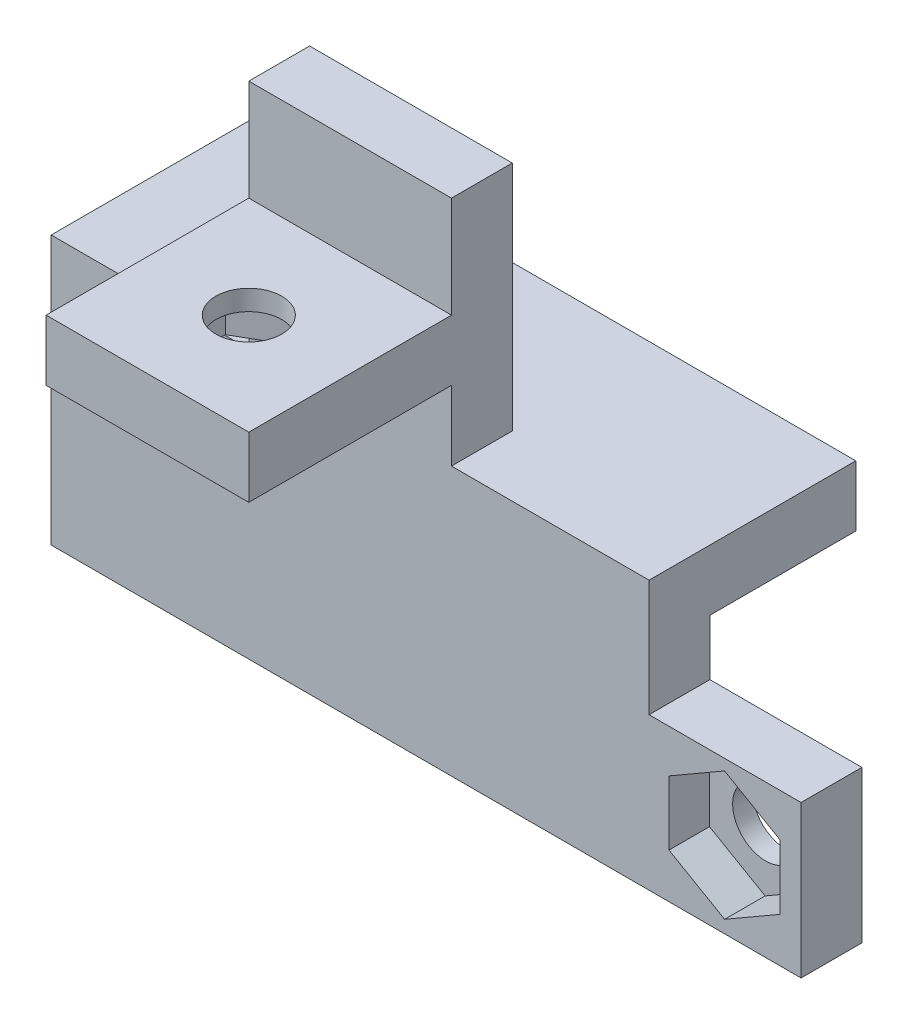
SolidWorks part; units mm, degrees
ref_plane "Alzado" through (0, 0, 0) normal (0, 0, 1) x (1, 0, 0)
ref_plane "Planta" through (0, 0, 0) normal (0, 1, 0) x (1, 0, 0)
ref_plane "Vista lateral" through (0, 0, 0) normal (1, 0, 0) x (0, 0, -1)
sketch "Croquis1" plane through (0, 0, 0) normal (0, 0, 1) x (1, 0, 0)
  line L0 (-40.4588, -20.95) -> (-40.4588, -24.7) construction
  line L1 (-40.4588, -24.7) -> (-77.4588, -24.7)
  line L2 (-77.4588, -14.45) -> (-47.9588, -14.45)
  line L4 (-40.4588, -24.7) -> (-40.4588, -17.2)
  line L5 (-40.4588, -17.2) -> (-47.9588, -17.2)
  line L7 (-47.9588, -17.2) -> (-47.9588, -14.45)
  line L8 (-77.4588, -24.7) -> (-77.4588, -14.45)
  circle A0 centre (-44.2088, -20.95) radius 1.625
  dimension "D1" = 3.25
  dimension "D2" = 40.4588
  dimension "D3" = 44.2088
  dimension "D4" = 47.9588
  dimension "D5" = 77.4588
  dimension "D6" = 14.45
  dimension "D7" = 17.2
extrude "Saliente-Extruir1" add sketch "Croquis1" along normal blind 3
sketch "Croquis2" plane through (0, 0, 3) normal (0, 0, 1) x (1, 0, 0)
  line L0 (-40.4588, -24.7) -> (-40.4588, -17.2) construction
  line L1 (-44.2325, -17.739) -> (-46.9778, -19.324)
  line L2 (-46.9778, -19.324) -> (-46.9778, -22.494)
  line L3 (-46.9778, -22.494) -> (-44.2325, -24.079)
  line L4 (-44.2325, -24.079) -> (-41.4872, -22.494)
  line L5 (-41.4872, -22.494) -> (-41.4872, -19.324)
  line L6 (-41.4872, -19.324) -> (-44.2325, -17.739)
  line L7 (-47.9588, -14.45) -> (-77.4588, -14.45) construction
  circle A0 centre (-44.2325, -20.909) radius 2.7453 construction
  dimension "D1" = 5.4906
  dimension "D2" = 1.0284
  dimension "D3" = 3.289
extrude "Cortar-Extruir1" cut sketch "Croquis2" against normal blind 2
sketch "Croquis4" plane through (0, -14.45, 0) normal (0, 1, 0) x (1, 0, 0)
  line L0 (-77.3588, 7.2) -> (-77.4588, 7.2) construction
  line L1 (-77.4588, -3) -> (-77.4588, 0) construction
  line L2 (-47.9588, -3) -> (-77.4588, -3)
  line L3 (-47.9588, -3) -> (-47.9588, 7.2)
  line L4 (-47.9588, 7.2) -> (-77.4588, 7.2)
  line L5 (-77.4588, -3) -> (-77.4588, 7.2)
  line L6 (-47.9588, 0) -> (-77.4588, 0) construction
  dimension "D1" = 29.5
  dimension "D2" = 7.2
  dimension "D3" = 3
extrude "Saliente-Extruir2" add sketch "Croquis4" along normal blind 3
sketch "Croquis6" plane through (0, 0, 3) normal (0, 0, 1) x (1, 0, 0)
  line L0 (-77.4588, -11.45) -> (-47.9588, -11.45) construction
  line L1 (-47.9588, -11.45) -> (-62.7088, -11.45) construction
  line L2 (-47.9588, -17.2) -> (-47.9588, -11.45) construction
  line L3 (-62.7088, -11.45) -> (-62.7088, -5) construction
  line L4 (-62.7088, -11.45) -> (-67.7088, -11.45)
  line L5 (-62.7088, -11.45) -> (-57.7088, -11.45)
  line L6 (-57.7088, -11.45) -> (-57.7088, -5)
  line L7 (-57.7088, -5) -> (-67.7088, -5)
  line L8 (-67.7088, -5) -> (-67.7088, -11.45)
  line L9 (-46.9778, -19.324) -> (-46.9778, -22.494) construction
  dimension "D1" = 10.731
  dimension "D2" = 12.739
extrude "Saliente-Extruir3" add sketch "Croquis6" against normal up to vertex (3 mm away)
sketch "Croquis7" plane through (0, -5, 0) normal (0, 1, 0) x (1, 0, 0)
  line L0 (-57.7088, 0) -> (-67.7088, 0) construction
  line L1 (-67.7088, 0) -> (-57.7088, 0)
  line L2 (-67.7088, 0) -> (-67.7088, -3)
  line L3 (-67.7088, -3) -> (-57.7088, -3)
  line L4 (-57.7088, 0) -> (-57.7088, -3)
  line L5 (-57.7088, 0) -> (-57.7088, -3) construction
  line L6 (-57.7088, -3) -> (-67.7088, -3) construction
  dimension "D1" = 10
extrude "Saliente-Extruir4" add sketch "Croquis7" along normal up to vertex (5 mm away)
sketch "Croquis9" plane through (0, 0, 3) normal (0, 0, 1) x (1, 0, 0)
  line L0 (-57.2795, -5) -> (-59.2014, -5) construction
  line L1 (-57.7088, -8) -> (-57.7088, -5)
  line L2 (-57.7088, -11.45) -> (-57.7088, 0) construction
  line L3 (-57.7088, -8) -> (-67.7088, -8)
  line L4 (-67.7088, 0) -> (-67.7088, -11.45) construction
  line L5 (-67.7088, -8) -> (-67.7088, -5)
  line L6 (-67.7088, -5) -> (-57.7088, -5)
  line L8 (-40.4588, -17.2) -> (-47.9588, -17.2) construction
  dimension "D1" = 9.2
  dimension "D2" = 12.2
extrude "Saliente-Extruir5" add sketch "Croquis9" along normal blind 10
sketch "Croquis10" plane through (0, -8, 0) normal (0, -1, 0) x (1, 0, 0)
  line L0 (-57.7088, 3) -> (-67.7088, 13) construction
  line L1 (-77.4588, 3) -> (-40.4588, 3) construction
  line L2 (-57.7088, 13) -> (-57.7088, 3) construction
  line L3 (-67.7088, 13) -> (-57.7088, 13) construction
  circle A0 centre (-62.7088, 8) radius 1.625
  dimension "D1" = 3.25
  dimension "D2" = 5
extrude "Cortar-Extruir2" cut sketch "Croquis10" against normal up to vertex (3 mm away)
sketch "Croquis11" plane through (0, -8, 0) normal (0, -1, 0) x (1, 0, 0)
  line L0 (-67.7088, 3) -> (-57.7088, 13) construction
  line L1 (-67.7088, 13) -> (-67.7088, 3) construction
  line L2 (-77.4588, 3) -> (-40.4588, 3) construction
  line L3 (-67.7088, 13) -> (-57.7088, 13) construction
  line L4 (-57.7088, 13) -> (-57.7088, 3) construction
  line L5 (-62.7088, 4.83) -> (-59.9635, 6.415)
  line L6 (-59.9635, 6.415) -> (-59.9635, 9.585)
  line L7 (-59.9635, 9.585) -> (-62.7088, 11.17)
  line L8 (-62.7088, 11.17) -> (-65.4541, 9.585)
  line L9 (-65.4541, 9.585) -> (-65.4541, 6.415)
  line L10 (-65.4541, 6.415) -> (-62.7088, 4.83)
  circle A0 centre (-62.7088, 8) radius 2.7453 construction
  dimension "D1" = 5.4906
  dimension "D2" = 2.2547
extrude "Cortar-Extruir3" cut sketch "Croquis11" against normal blind 2
